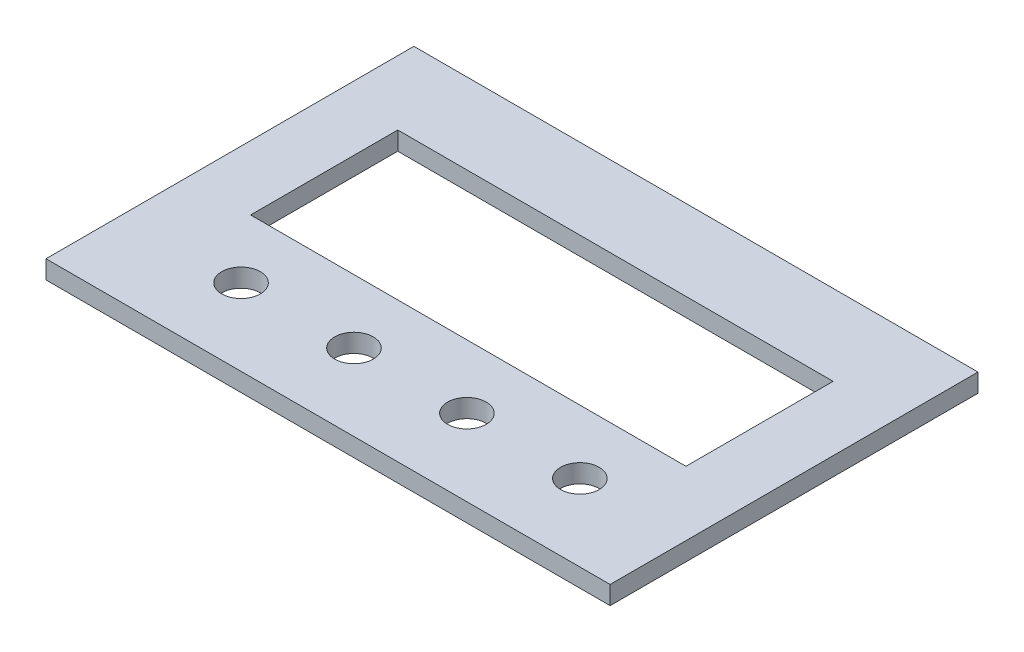
SolidWorks part; units mm, degrees
ref_plane "Front Plane" through (0, 0, 0) normal (0, 0, 1) x (1, 0, 0)
ref_plane "Top Plane" through (0, 0, 0) normal (0, 1, 0) x (1, 0, 0)
ref_plane "Right Plane" through (0, 0, 0) normal (1, 0, 0) x (0, 0, -1)
sketch "Sketch1" plane through (0, 0, 0) normal (0, 1, 0) x (1, 0, 0)
  line L0 (-72.4246, -17.491) -> (81.5515, -17.491) construction
  line L1 (-46, 30) -> (46, 30)
  line L2 (-46, 30) -> (-46, -30)
  line L3 (-46, -30) -> (46, -30)
  line L4 (46, 30) -> (46, -30)
  line L5 (-46, 30) -> (46, -30) construction
  line L6 (-46, -30) -> (46, 30) construction
  line L7 (-35.5, 16.87) -> (35.5, 16.87)
  line L8 (-35.5, 16.87) -> (-35.5, -7.13)
  line L9 (-35.5, -7.13) -> (35.5, -7.13)
  line L10 (35.5, 16.87) -> (35.5, -7.13)
  circle A0 centre (-26.7, -17.491) radius 3.15
  circle A1 centre (-8.28, -17.491) radius 3.15
  circle A2 centre (10.14, -17.491) radius 3.15
  circle A3 centre (28.56, -17.491) radius 3.15
  point P0 (0, 0)
  dimension "D5" = 6.3
  dimension "D6" = 6.3
  dimension "D7" = 6.3
  dimension "D8" = 6.3
  dimension "D10" = 18.42
  dimension "D12" = 18.42
  dimension "D1" = 92
  dimension "D2" = 60
  dimension "D3" = 71
  dimension "D4" = 24
  dimension "D9" = 19.3
  dimension "D11" = 18.42
  dimension "D13" = 10.5
  dimension "D14" = 13.13
extrude "Boss-Extrude1" add sketch "Sketch1" along normal blind 3
